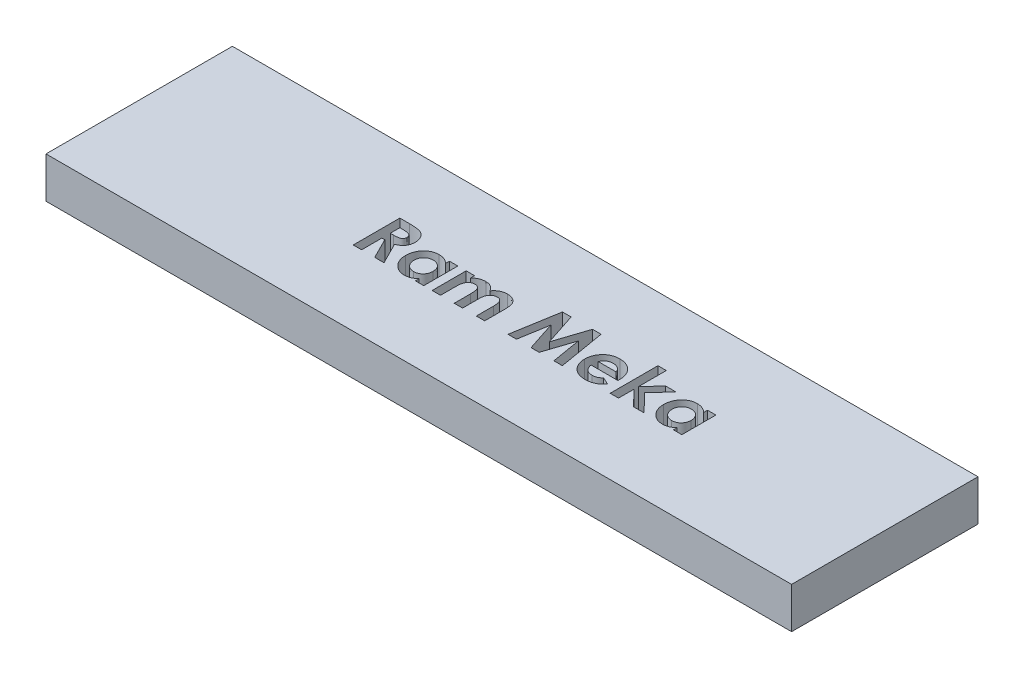
SolidWorks part; units mm, degrees
ref_plane "Front Plane" through (0, 0, 0) normal (0, 0, 1) x (1, 0, 0)
ref_plane "Top Plane" through (0, 0, 0) normal (0, 1, 0) x (1, 0, 0)
ref_plane "Right Plane" through (0, 0, 0) normal (1, 0, 0) x (0, 0, -1)
sketch "Sketch1" plane through (0, 0, 0) normal (0, 1, 0) x (1, 0, 0)
  line L1 (25.4, -6.35) -> (-25.4, -6.35)
  line L2 (25.4, -6.35) -> (25.4, 6.35)
  line L3 (25.4, 6.35) -> (-25.4, 6.35)
  line L4 (-25.4, -6.35) -> (-25.4, 6.35)
  line L5 (25.4, -6.35) -> (-25.4, 6.35) construction
  line L6 (25.4, 6.35) -> (-25.4, -6.35) construction
  text T0 "<b>Ram Meka</b>"
  point P0 (0, 0)
  dimension "D1" = 50.8
  dimension "D2" = 12.7
extrude "Boss-Extrude2" add sketch "Sketch1" against normal blind 2.794 contours L4 L1 L2 L3
sketch "Sketch3" plane through (0, 0, 0) normal (0, 1, 0) x (1, 0, 0)
  text T0 "<b>Ram Meka</b>"
extrude "Cut-Extrude1" cut sketch "Sketch3" against normal through all
